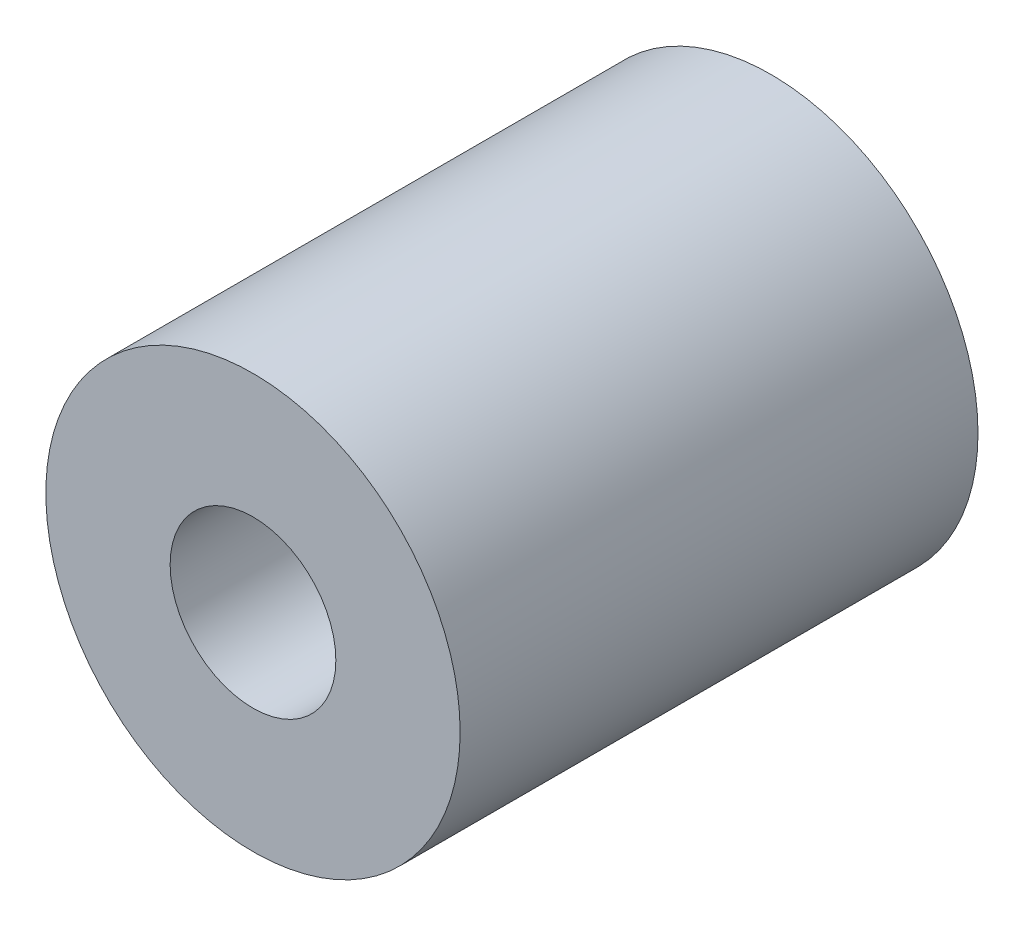
SolidWorks part; units mm, degrees
ref_plane "前视基准面" through (0, 0, 0) normal (0, 0, 1) x (1, 0, 0)
ref_plane "上视基准面" through (0, 0, 0) normal (0, 1, 0) x (1, 0, 0)
ref_plane "右视基准面" through (0, 0, 0) normal (1, 0, 0) x (0, 0, -1)
other "Configuration Table"
sketch "Profile_1" plane through (0, 0, 0) normal (0, 0, 1) x (1, 0, 0)
  circle A0 centre (0, 0) radius 10
  circle A1 centre (0, 0) radius 3
extrude "Six_bore" add sketch "Profile_1" along normal blind 12.5 from offset 7.5
sketch "Profile_2" plane through (0, 0, 0) normal (0, 0, 1) x (1, 0, 0)
  circle A0 centre (0, 0) radius 10
  circle A1 centre (0, 0) radius 4
extrude "Eight_bore" add sketch "Profile_2" along normal blind 12.5 from offset 20
